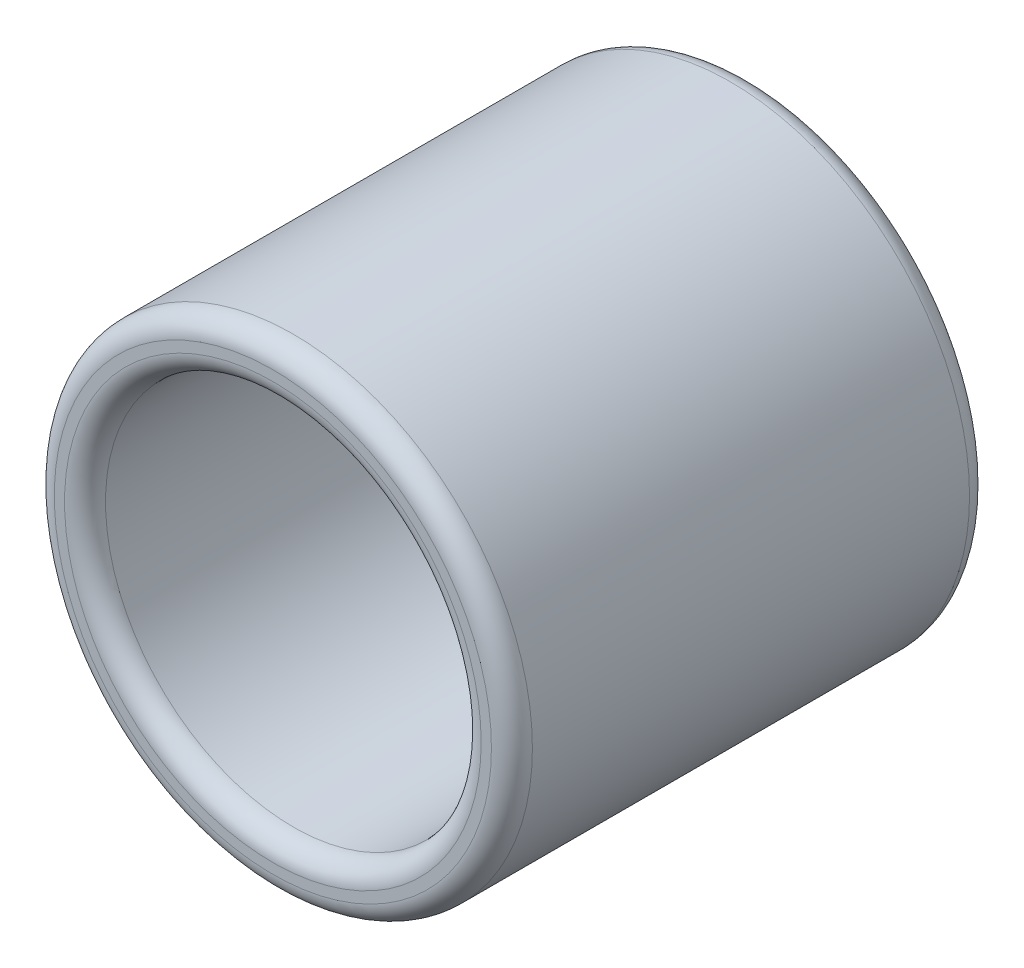
SolidWorks part; units mm, degrees
ref_plane "Front Plane" through (0, 0, 0) normal (0, 0, 1) x (1, 0, 0)
ref_plane "Top Plane" through (0, 0, 0) normal (0, 1, 0) x (1, 0, 0)
ref_plane "Right Plane" through (0, 0, 0) normal (1, 0, 0) x (0, 0, -1)
sketch "Sketch1" plane through (0, 0, 0) normal (0, 0, 1) x (1, 0, 0)
  circle A0 centre (0, 0) radius 3.5
  dimension "D1" = 7
extrude "Boss-Extrude1" add sketch "Sketch1" along normal blind 7
sketch "Sketch2" plane through (0, 0, 0) normal (0, 0, -1) x (-1, 0, 0)
  circle A0 centre (0, 0) radius 2.75
  dimension "D1" = 5.5
extrude "Cut-Extrude1" cut sketch "Sketch2" against normal blind 7
fillet "Fillet2" radius 0.3 3 edges at (3.5, 0, 0) (-2.75, 0, 7) (-2.75, 0, 0)
fillet "Fillet3" radius 0.3 1 edges at (3.5, 0, 7)
